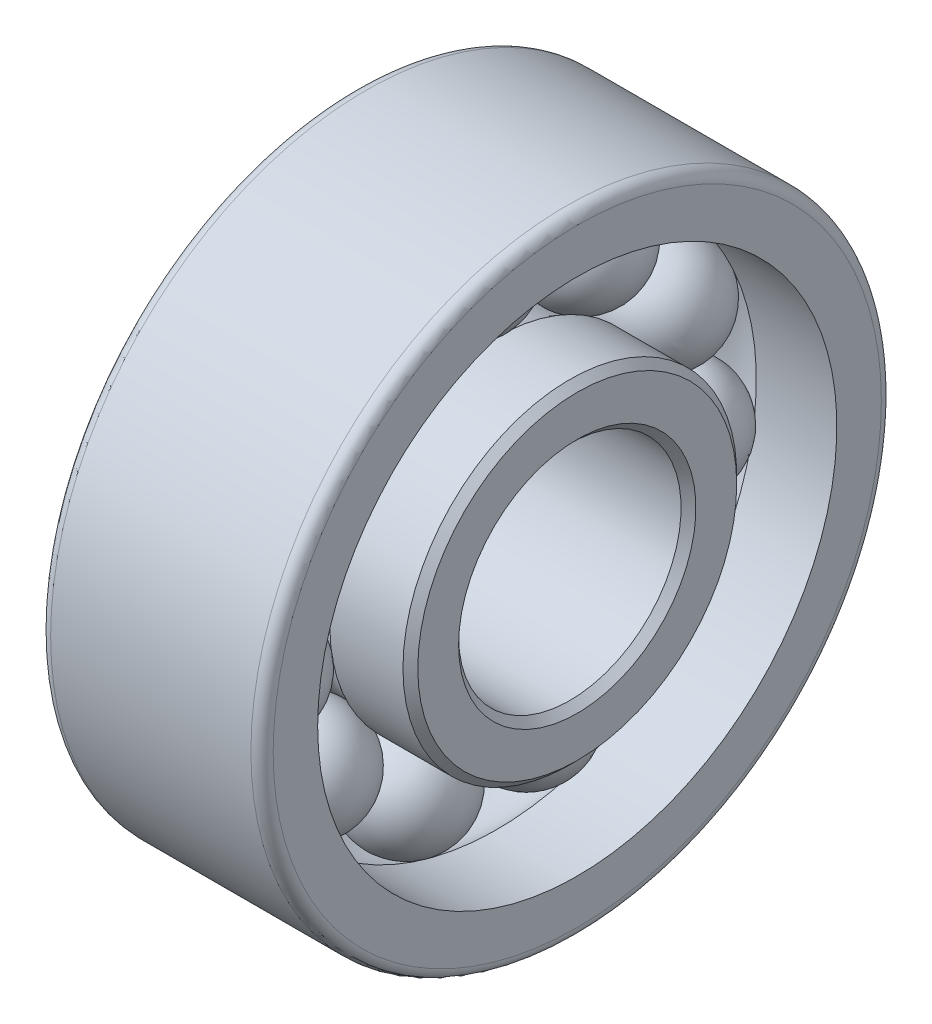
SolidWorks part; units mm, degrees
ref_plane "Спереди" through (0, 0, 0) normal (0, 0, 1) x (1, 0, 0)
ref_plane "Сверху" through (0, 0, 0) normal (0, 1, 0) x (1, 0, 0)
ref_plane "Справа" through (0, 0, 0) normal (1, 0, 0) x (0, 0, -1)
sketch "Эскиз1" plane through (0, 0, 0) normal (0, 0, 1) x (1, 0, 0)
  line L0 (-1.0669, -3) -> (5.2077, -3) construction
  line L1 (0, 0) -> (6, 0)
  line L2 (0, 0) -> (0, 1.5)
  line L3 (0, 1.5) -> (2.1708, 1.5)
  line L4 (6, 0) -> (6, 1.5)
  line L5 (0, 4) -> (2.1708, 4)
  line L6 (0, 4) -> (0, 5.5)
  line L7 (0, 5.5) -> (6, 5.5)
  line L8 (6, 4) -> (6, 5.5)
  line L9 (3.8292, 4) -> (6, 4)
  line L10 (3.8292, 1.5) -> (6, 1.5)
  arc A0 (2.1708, 1.5) -> (3.8292, 1.5) centre (3, 2.75) ccw
  arc A1 (3.8292, 4) -> (2.1708, 4) centre (3, 2.75) ccw
  dimension "D7" = 1.25
  dimension "D1" = 3
  dimension "D2" = 6
  dimension "D3" = 1.5
  dimension "D4" = 6
  dimension "D5" = 1.5
  dimension "D6" = 8.5
revolve "Повернуть1" add sketch "Эскиз1" angle 360 about L0
sketch "Эскиз2" plane through (0, 0, 0) normal (0, 0, 1) x (1, 0, 0)
  line L0 (3, 4.25) -> (3, 1.25) construction
  line L1 (3, 4.25) -> (3, 1.25)
  arc A0 (3, 4.25) -> (3, 1.25) centre (3, 2.75) ccw
revolve "Повернуть2" add sketch "Эскиз2" angle 360 about L0
pattern_circular "Круговой массив5" count 11 over 360 about axis through (0, -3, 0) along (1, 0, 0) of bodies 105
fillet "Скругление1" radius 0.3 2 edges at (6, -3, 8.5) (0, -3, 8.5)
chamfer "Фаска1" distance 0.2 angle 45 4 edges at (0, -3, 3) (6, -3, 3) (6, -3, 4.5) (0, -3, 4.5)
